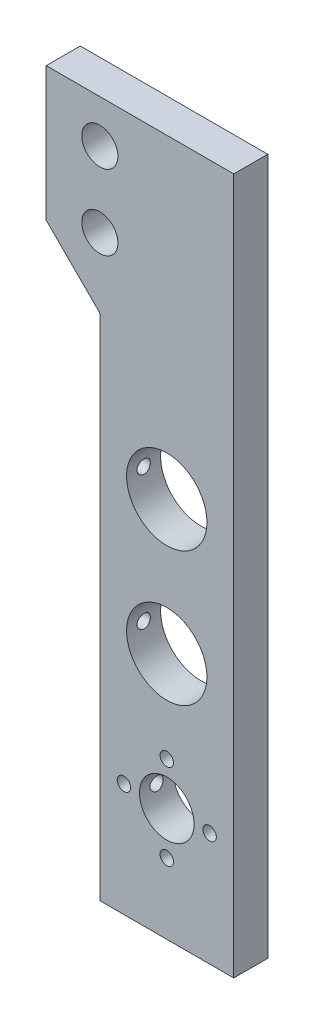
SolidWorks part; units mm, degrees
material "6061 Alloy"
ref_plane "Front Plane" through (0, 0, 0) normal (0, 0, 1) x (1, 0, 0)
ref_plane "Top Plane" through (0, 0, 0) normal (0, 1, 0) x (1, 0, 0)
ref_plane "Right Plane" through (0, 0, 0) normal (1, 0, 0) x (0, 0, -1)
sketch "Sketch2" plane through (0, 0, 0) normal (0, 0, 1) x (1, 0, 0)
  line L0 (0, 0) -> (0, -21.15) construction
  line L1 (-12.5, -21.15) -> (12.5, -21.15)
  line L2 (-12.5, -21.15) -> (-12.5, 108.85)
  line L3 (-12.5, 108.85) -> (12.5, 108.85)
  line L4 (12.5, -21.15) -> (12.5, 108.85)
  circle A0 centre (0, 0) radius 5.1
  circle A1 centre (0, 25) radius 7.5
  circle A2 centre (0, 50) radius 7.5
  dimension "D1" = 10.2
  dimension "D5" = 25
  dimension "D7" = 15
  dimension "D2" = 21.15
  dimension "D3" = 25
  dimension "D4" = 130
  dimension "D6" = 25
extrude "Boss-Extrude1" add sketch "Sketch2" along normal blind 6.35
sketch "Sketch3" plane through (-12.5, 0, 0) normal (-1, 0, 0) x (0, 0, 1)
  line L0 (6.35, -5.1) -> (6.35, 5.1) construction
  line L1 (6.35, 17.5) -> (6.35, 32.5) construction
  line L2 (6.35, 42.5) -> (6.35, 57.5) construction
  line L3 (6.35, -5.1) -> (6.35, 5.1) construction
  line L4 (6.35, 17.5) -> (6.35, 32.5) construction
  line L5 (6.35, 42.5) -> (6.35, 57.5) construction
  line L6 (3.175, 108.85) -> (3.175, -21.15) construction
  line L7 (6.35, 108.85) -> (0, 108.85) construction
  line L8 (6.35, -21.15) -> (0, -21.15) construction
  line L9 (6.35, 0) -> (3.175, 0) construction
  line L10 (6.35, 25) -> (3.175, 25) construction
  line L11 (6.35, 50) -> (3.175, 50) construction
  point P13 (3.175, 0)
  point P16 (3.175, 25)
  point P18 (3.175, 50)
hole_wizard "Tap Drill for M3x0.5 Tap1" positions "Sketch3" profile "Sketch4" hole size "M3x0.5" standard "ANSI Metric"
sketch "Sketch4" plane through (-12.5, 50, 3.175) normal (0, 1, 0) x (0, 0, 1)
  line L0 (0, 0) -> (0, 13.2511)
  line L1 (0, 13.2511) -> (1.25, 12.5)
  line L2 (1.25, 12.5) -> (1.25, 0)
  line L5 (1.25, 0) -> (0, 0)
  line L10 (0, 13.2511) -> (-1.25, 12.5) construction
  line L11 (0, -6.35) -> (0, 107.95) construction
  dimension "Hole Dia." = 2.5
  dimension "Hole Depth" = 12.5
  dimension "Drill Angle" = 118
sketch "Sketch8" plane through (0, 0, 0) normal (0, 0, -1) x (-1, 0, 0)
  line L0 (12.5, 73.85) -> (22.5, 83.85)
  line L1 (12.5, 108.85) -> (12.5, -21.15) construction
  line L2 (22.5, 83.85) -> (22.5, 108.85)
  line L3 (22.5, 108.85) -> (12.5, 108.85)
  line L4 (12.5, 108.85) -> (12.5, 73.85)
  dimension "D1" = 10
  dimension "D2" = 45
  dimension "D3" = 35
extrude "Boss-Extrude2" add sketch "Sketch8" against normal up to surface (6.35 mm away) up to face at (0, 43.85, 6.35)
sketch "Sketch5" plane through (0, 0, 6.35) normal (0, 0, 1) x (1, 0, 0)
  line L0 (-12.5, 108.85) -> (-12.5, 78.85) construction
  line L1 (12.5, 108.85) -> (-22.5, 108.85) construction
  line L2 (-22.5, 108.85) -> (-22.5, 83.85) construction
  point P4 (-12.5, 100.85)
  point P8 (-12.5, 86.85)
  dimension "D1" = 30
  dimension "D2" = 10
  dimension "D3" = 8
  dimension "D4" = 8
hole_wizard "1/4 Clearance Hole1" positions "Sketch6" profile "Sketch7" hole size "1/4" standard "ANSI Inch" end condition through all
sketch "Sketch6" plane through (0, 0, 6.35) normal (0, 0, 1) x (1, 0, 0)
  point P0 (-12.5, 86.85)
  point P3 (-12.5, 100.85)
sketch "Sketch7" plane through (-12.5, 86.85, 6.35) normal (1, 0, 0) x (0, -1, 0)
  line L0 (0, 0) -> (0, 6.35)
  line L1 (0, 6.35) -> (3.3782, 6.35)
  line L2 (3.3782, 6.35) -> (3.3782, 0)
  line L5 (3.3782, 0) -> (0, 0)
  line L11 (0, -6.35) -> (0, 107.95) construction
  dimension "Thru Hole Dia." = 6.7564
  dimension "Thru Hole Depth" = 6.35
sketch "Sketch9" plane through (0, 0, 6.35) normal (0, 0, 1) x (1, 0, 0)
  circle A0 centre (0, 0) radius 8 construction
  point P3 (0, 8)
  point P4 (8, 0)
  point P5 (0, -8)
  point P6 (-8, 0)
  dimension "D1" = 16
hole_wizard "Tap Drill for M3x0.5 Tap2" positions "Sketch9" profile "Sketch10" hole size "M3x0.5" standard "ANSI Metric" end condition through all
sketch "Sketch10" plane through (-8, 0, 6.35) normal (1, 0, 0) x (0, -1, 0)
  line L0 (0, 0) -> (0, 6.35)
  line L1 (0, 6.35) -> (1.25, 6.35)
  line L2 (1.25, 6.35) -> (1.25, 0)
  line L5 (1.25, 0) -> (0, 0)
  line L11 (0, -6.35) -> (0, 107.95) construction
  dimension "Thru Hole Dia." = 2.5
  dimension "Thru Hole Depth" = 6.35
